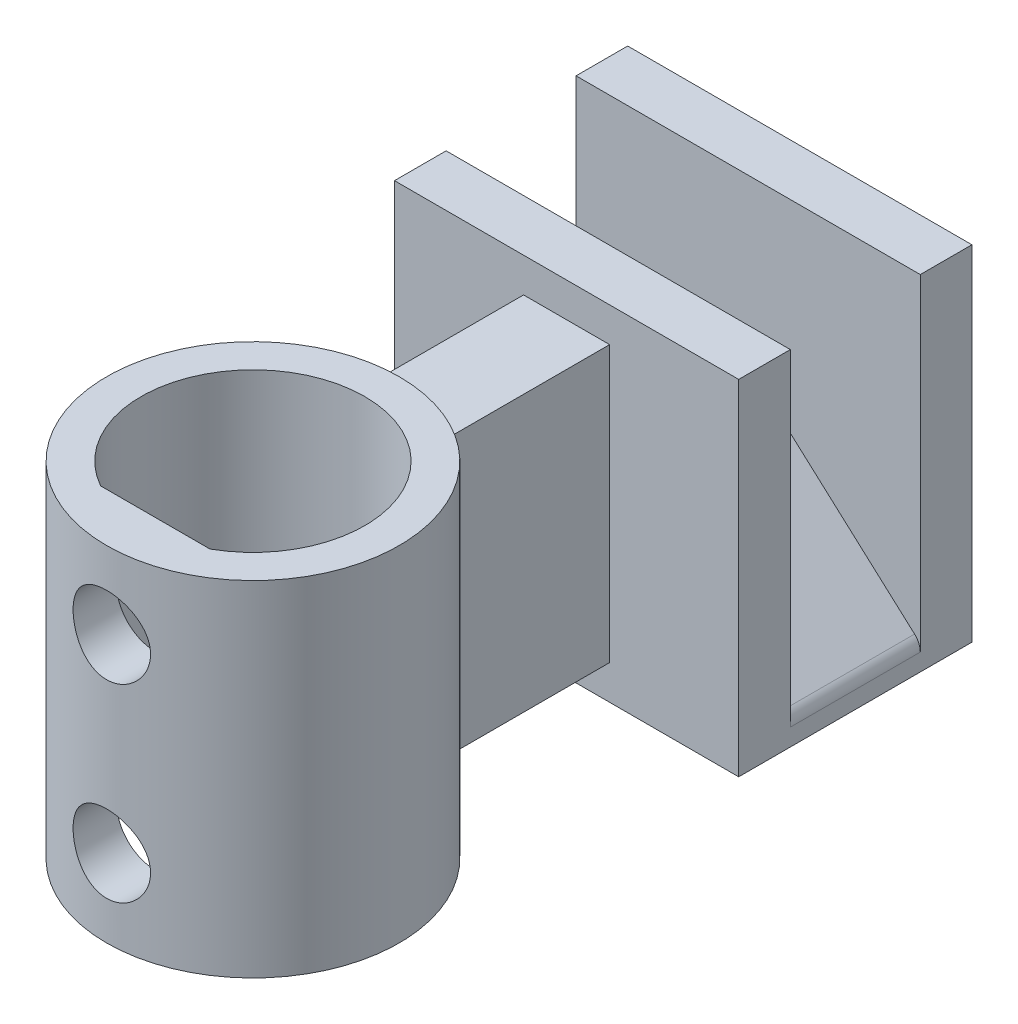
SolidWorks part; units mm, degrees
ref_plane "Front Plane" through (0, 0, 0) normal (0, 0, 1) x (1, 0, 0)
ref_plane "Top Plane" through (0, 0, 0) normal (0, 1, 0) x (1, 0, 0)
ref_plane "Right Plane" through (0, 0, 0) normal (1, 0, 0) x (0, 0, -1)
sketch "Sketch2" plane through (0, 0, 0) normal (0, 0, 1) x (1, 0, 0)
  line L1 (-10, -5) -> (10, -5)
  line L2 (-10, -5) -> (-10, 5)
  line L3 (-10, 5) -> (10, 5)
  line L4 (10, -5) -> (10, 5)
  line L5 (-10, -5) -> (10, 5) construction
  line L6 (-10, 5) -> (10, -5) construction
  point P0 (0, 0)
  dimension "D1" = 10
  dimension "D2" = 20
extrude "Boss-Extrude1" add sketch "Sketch2" along normal mid plane 7.55
chamfer "Chamfer1" distance 9.5 angle 42 2 edges at (10, 5, 0) (-10, 5, 0)
fillet "Fillet3" radius 1 4 edges at (-10, -3.5538, 0) (10, -3.5538, 0) (0.5, 5, 0) (-0.5, 5, 0)
sketch "Sketch3" plane through (0, 0, 3.775) normal (0, 0, 1) x (1, 0, 0)
  line L0 (-10, -5) -> (10, -5) construction
  line L1 (-10, 15) -> (10, 15)
  line L2 (-10, 15) -> (-10, -5)
  line L3 (-10, -5) -> (10, -5)
  line L4 (10, 15) -> (10, -5)
  line L5 (-10, 15) -> (10, -5) construction
  line L6 (-10, -5) -> (10, 15) construction
  point P0 (0, 5)
  dimension "D1" = 20
  dimension "D2" = 20
extrude "Boss-Extrude2" add sketch "Sketch3" along normal blind 3
mirror "Mirror1" about plane through (0, 0, 0) normal (0, 0, 1) of "Boss-Extrude2"
sketch "Sketch6" plane through (0, 0, 0) normal (0, 1, 0) x (1, 0, 0)
  line L0 (-3.175, -30.6718) -> (3.175, -30.6718)
  arc A0 (3.175, -30.6718) -> (-3.175, -30.6718) centre (0, -25) ccw
  circle A1 centre (0, -25) radius 8.5
  dimension "D1" = 13
  dimension "D2" = 2
  dimension "D3" = 25
  dimension "D4" = 6.35
extrude "Boss-Extrude3" add sketch "Sketch6" along normal up to surface and the other way up to surface separate body up to face at (0, 15, 5.275) other way up to face at (0, -5, 0)
sketch "Sketch5" plane through (0, 0, 6.775) normal (0, 0, 1) x (1, 0, 0)
  line L0 (-10, -5) -> (10, -5) construction
  line L1 (-2.5, 13) -> (2.5, 13)
  line L2 (-2.5, 13) -> (-2.5, -3)
  line L3 (-2.5, -3) -> (2.5, -3)
  line L4 (2.5, 13) -> (2.5, -3)
  line L5 (-2.5, 13) -> (2.5, -3) construction
  line L6 (-2.5, -3) -> (2.5, 13) construction
  line L7 (10, 15) -> (-10, 15) construction
  point P0 (0, 5)
  dimension "D1" = 2
  dimension "D2" = 2
  dimension "D3" = 5
extrude "Boss-Extrude4" add sketch "Sketch5" along normal up to surface (10.101 mm away)
ref_plane "Plane1" through (0, 0, 20) normal (0, 0, 1) x (1, 0, 0)
sketch "Sketch7" plane through (0, 0, 20) normal (0, 0, 1) x (1, 0, 0)
  line L0 (-8.5, -5) -> (8.5, -5) construction
  line L1 (6.5, 15) -> (-6.5, 15) construction
  circle A0 centre (0, 10.5) radius 2.25
  circle A1 centre (0, -0.5) radius 2.25
  dimension "D1" = 4.5
  dimension "D2" = 4.5
  dimension "D3" = 4.5
  dimension "D4" = 4.5
extrude "Cut-Extrude1" cut sketch "Sketch7" along normal up to surface (13.1968 mm away)
